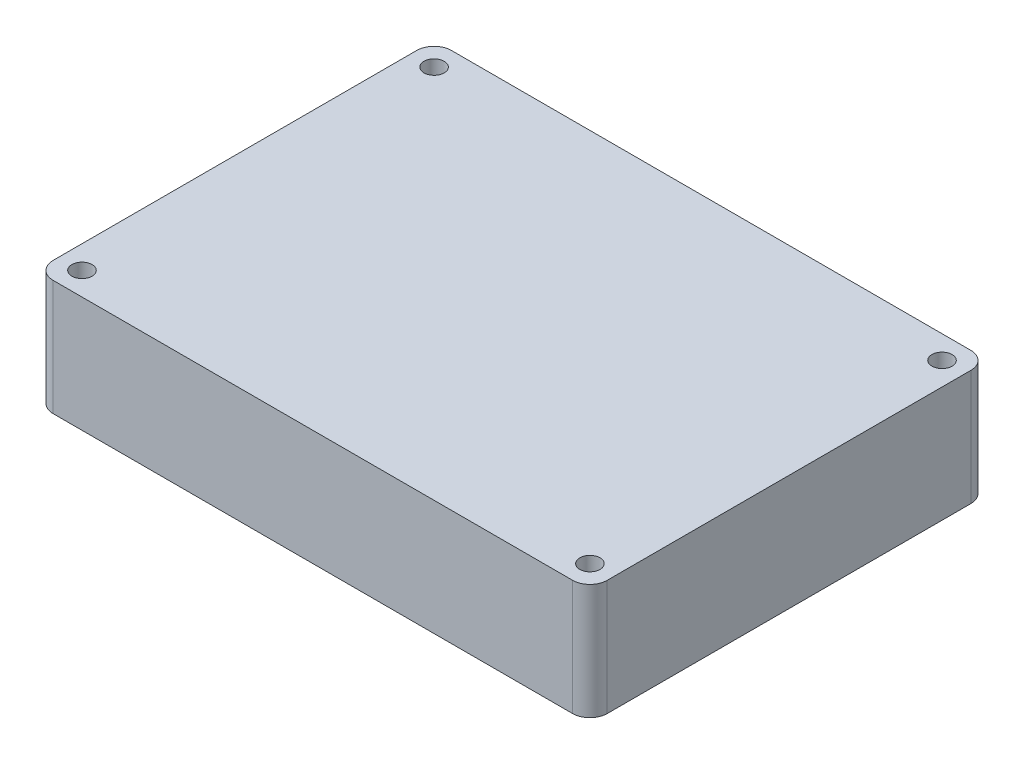
SolidWorks part; units mm, degrees
ref_plane "前视基准面" through (0, 0, 0) normal (0, 0, 1) x (1, 0, 0)
ref_plane "上视基准面" through (0, 0, 0) normal (0, 1, 0) x (1, 0, 0)
ref_plane "右视基准面" through (0, 0, 0) normal (1, 0, 0) x (0, 0, -1)
other "Configuration Table"
sketch "草图1" plane through (0, 0, 0) normal (0, 1, 0) x (1, 0, 0)
  line L1 (-44, -30.5) -> (44, -30.5) construction
  line L2 (-44, -30.5) -> (-44, 30.5) construction
  line L3 (-44, 30.5) -> (44, 30.5) construction
  line L4 (44, -30.5) -> (44, 30.5) construction
  line L5 (-44, -30.5) -> (44, 30.5) construction
  line L6 (-44, 30.5) -> (44, -30.5) construction
  line L7 (-48, -34.5) -> (48, -34.5)
  line L8 (-48, -34.5) -> (-48, 34.5)
  line L9 (-48, 34.5) -> (48, 34.5)
  line L10 (48, -34.5) -> (48, 34.5)
  line L11 (-48, -34.5) -> (48, 34.5) construction
  line L12 (-48, 34.5) -> (48, -34.5) construction
  circle A0 centre (-44, 30.5) radius 1.75
  circle A1 centre (44, 30.5) radius 1.75
  circle A2 centre (-44, -30.5) radius 1.75
  circle A3 centre (44, -30.5) radius 1.75
  point P0 (0, 0)
  point P10 (0, 0)
  dimension "D3" = 3.5
  dimension "D1" = 88
  dimension "D2" = 61
  dimension "D4" = 4
  dimension "D5" = 4
extrude "凸台-拉伸1" add sketch "草图1" along normal blind 20
fillet "圆角1" radius 3 4 edges at (-48, 10, 34.5) (-48, 10, -34.5) (48, 10, -34.5) (48, 10, 34.5)
